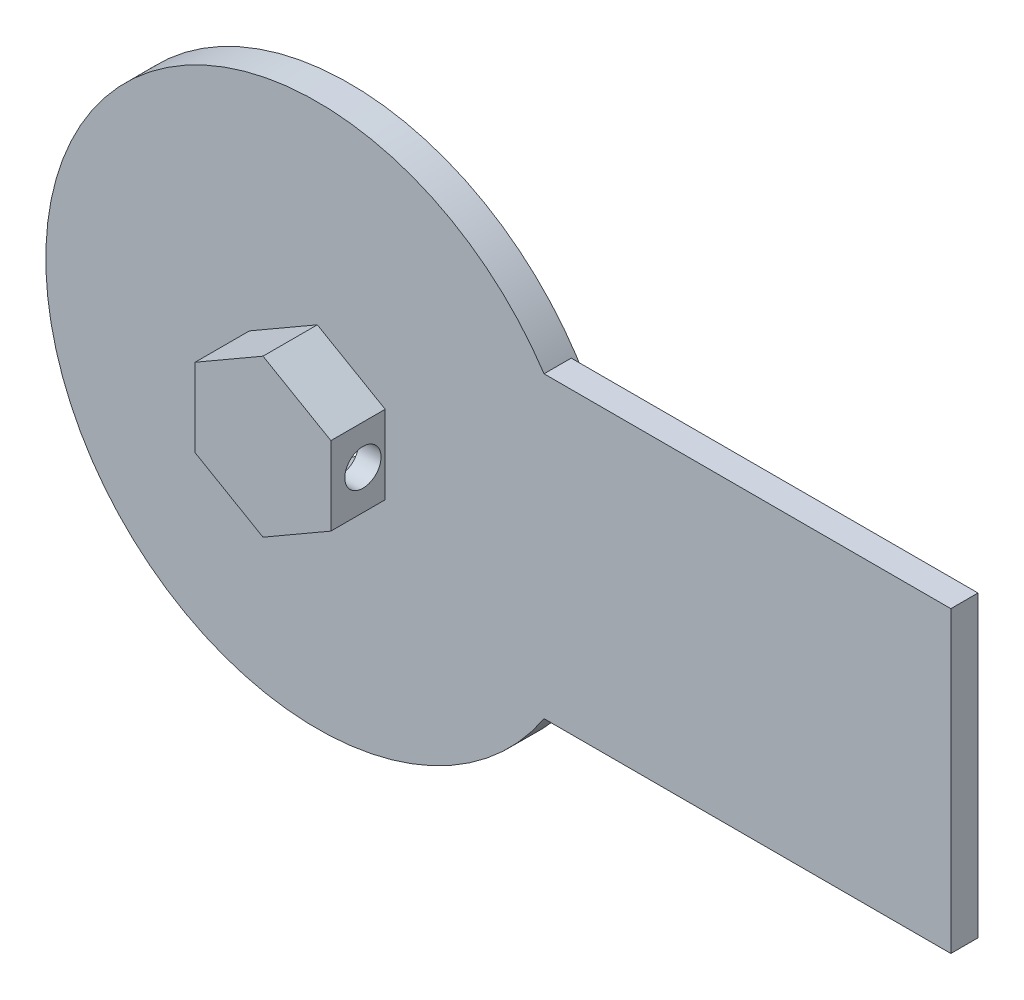
SolidWorks part; units mm, degrees
ref_plane "前视基准面" through (0, 0, 0) normal (0, 0, 1) x (1, 0, 0)
ref_plane "上视基准面" through (0, 0, 0) normal (0, 1, 0) x (1, 0, 0)
ref_plane "右视基准面" through (0, 0, 0) normal (1, 0, 0) x (0, 0, -1)
sketch "Sketch1" plane through (0, 0, 0) normal (0, 0, 1) x (1, 0, 0)
  circle A0 centre (0, 0) radius 30
extrude "Boss-Extrude1" add sketch "Sketch1" along normal blind 3.54
sketch "Sketch3" plane through (0, 0, 3.54) normal (0, 0, 1) x (1, 0, 0)
  circle A1 centre (12, 5) radius 4
  dimension "D1" = 5
  dimension "D2" = 12
sketch "Sketch4" plane through (0, 0, 3.54) normal (0, 0, 1) x (1, 0, 0)
  line L0 (25.7688, 0) -> (75.3766, 0) construction
  line L1 (25.0549, 16.5) -> (70, 16.5)
  line L2 (25.0549, -16.5) -> (70, -16.5)
  line L3 (30, 0) -> (30, 16.5) construction
  line L4 (70, 16.5) -> (70, -16.5)
  circle A0 centre (0, 0) radius 30 construction
  arc A1 (25.0549, 16.5) -> (25.0549, -16.5) centre (0, 0) cw
  dimension "D1" = 16.5
  dimension "D2" = 40
extrude "Boss-Extrude4" add sketch "Sketch4" against normal blind 3
sketch "Sketch9" plane through (0, 0, 0) normal (0, 0, -1) x (-1, 0, 0)
  line L1 (0, 5.7735) -> (-5, 2.8868)
  line L2 (-5, 2.8868) -> (-5, -2.8868)
  line L3 (-5, -2.8868) -> (0, -5.7735)
  line L4 (0, -5.7735) -> (5, -2.8868)
  line L5 (5, -2.8868) -> (5, 2.8868)
  line L6 (5, 2.8868) -> (0, 5.7735)
  circle A0 centre (0, 0) radius 5 construction
extrude "Cut-Extrude3" cut sketch "Sketch9" against normal blind 6
sketch "Sketch10" plane through (0, 0, 3.54) normal (0, 0, 1) x (1, 0, 0)
  line L1 (0, 5.7735) -> (-5, 2.8868)
  line L2 (-5, 2.8868) -> (-5, -2.8868)
  line L3 (-5, -2.8868) -> (0, -5.7735)
  line L4 (0, -5.7735) -> (5, -2.8868)
  line L5 (5, -2.8868) -> (5, 2.8868)
  line L6 (5, 2.8868) -> (0, 5.7735)
  line L7 (0, 8.6603) -> (-7.5, 4.3301)
  line L8 (-7.5, 4.3301) -> (-7.5, -4.3301)
  line L9 (-7.5, -4.3301) -> (0, -8.6603)
  line L10 (0, -8.6603) -> (7.5, -4.3301)
  line L11 (7.5, -4.3301) -> (7.5, 4.3301)
  line L12 (7.5, 4.3301) -> (0, 8.6603)
  circle A0 centre (0, 0) radius 5 construction
  circle A1 centre (0, 0) radius 7.5 construction
extrude "Boss-Extrude5" add sketch "Sketch10" along normal blind 6
sketch "Sketch11" plane through (0, 0, 9.54) normal (0, 0, 1) x (1, 0, 0)
  line L1 (0, 5.7735) -> (-5, 2.8868)
  line L2 (-5, 2.8868) -> (-5, -2.8868)
  line L3 (-5, -2.8868) -> (0, -5.7735)
  line L4 (0, -5.7735) -> (5, -2.8868)
  line L5 (5, -2.8868) -> (5, 2.8868)
  line L6 (5, 2.8868) -> (0, 5.7735)
  circle A0 centre (0, 0) radius 5 construction
extrude "Boss-Extrude6" add sketch "Sketch11" against normal blind 0.4
sketch "Sketch12" plane through (7.5, 0, 0) normal (1, 0, 0) x (0, 0, -1)
  line L0 (-3.54, -16.5) -> (-3.54, 16.5) construction
  circle A0 centre (-6, 0) radius 2
  dimension "D1" = 2.46
extrude "Cut-Extrude4" cut sketch "Sketch12" against normal up to next
